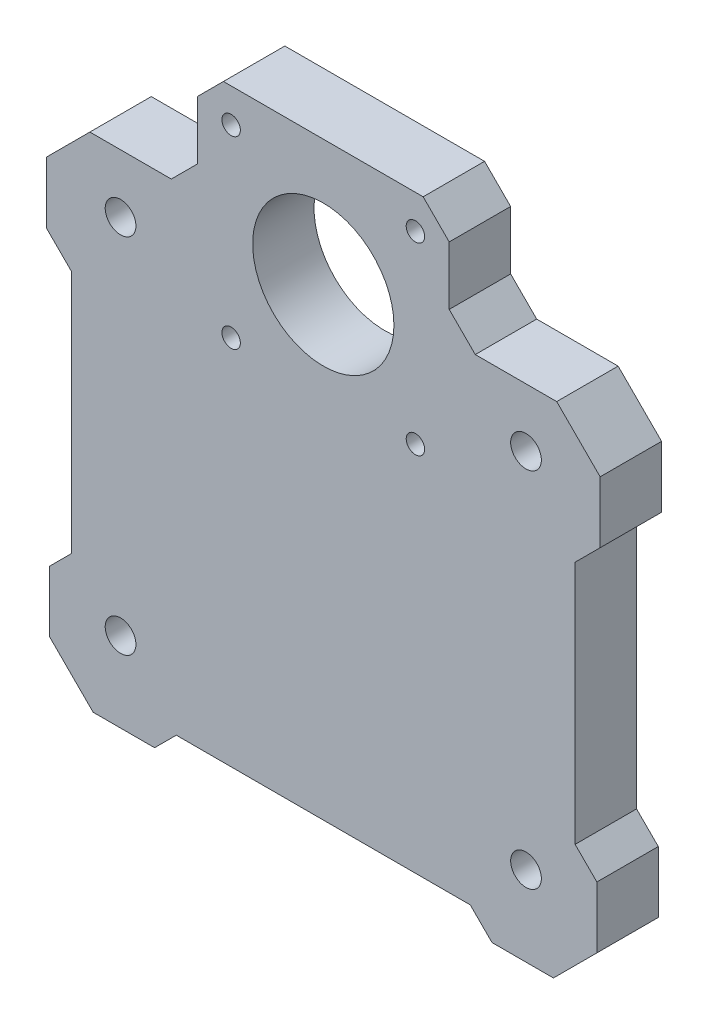
SolidWorks part; units mm, degrees
ref_plane "Alzado" through (0, 0, 0) normal (0, 0, 1) x (1, 0, 0)
ref_plane "Planta" through (0, 0, 0) normal (0, 1, 0) x (1, 0, 0)
ref_plane "Vista lateral" through (0, 0, 0) normal (1, 0, 0) x (0, 0, -1)
sketch "Croquis1" plane through (0, 0, 0) normal (0, 0, 1) x (1, 0, 0)
  line L0 (0, 0) -> (0, 36.5) construction
  line L5 (33, 29.5) -> (-33, 29.5)
  line L10 (33, 29.5) -> (33, -29.5)
  line L11 (33, -29.5) -> (-33, -29.5)
  line L12 (-33, 29.5) -> (-33, -29.5)
  line L13 (33, 29.5) -> (-33, -29.5) construction
  line L14 (33, -29.5) -> (-33, 29.5) construction
  line L15 (-41, 39) -> (41, 39)
  line L16 (-41, 39) -> (-41, -39)
  line L17 (-41, -39) -> (41, -39)
  line L18 (41, 39) -> (41, -39)
  line L19 (-41, 39) -> (41, -39) construction
  line L20 (-41, -39) -> (41, 39) construction
  line L22 (-20.5, 16) -> (20.5, 16)
  line L23 (-20.5, 16) -> (-20.5, 57)
  line L24 (-20.5, 57) -> (20.5, 57)
  line L25 (20.5, 16) -> (20.5, 57)
  line L26 (-20.5, 16) -> (20.5, 57) construction
  line L27 (-20.5, 57) -> (20.5, 16) construction
  circle A0 centre (-33, 29.5) radius 2.5
  circle A1 centre (33, 29.5) radius 2.5
  circle A2 centre (33, -29.5) radius 2.5
  circle A3 centre (-33, -29.5) radius 2.5
  circle A4 centre (0, 36.5) radius 11.5
  point P0 (0, 0)
  point P5 (0, 0)
  dimension "D5" = 36.5
  dimension "D6" = 23
  dimension "D1" = 66
  dimension "D2" = 59
  dimension "D3" = 78
  dimension "D4" = 82
  dimension "D7" = 41
  dimension "D8" = 41
extrude "Saliente-Extruir5" add sketch "Croquis1" along normal blind 10 contours A3 L11 A2 L10 A1 L5 L25 L22 L23 A0 L12 | A4 L5 L23 L22 L25 | A3 L12 A0 L5 L23 L15 L16 L17 L18 L25 A1 L10 A2 L11 | A4 L15 L25 L24 L23 | A4 L15 L23 L5 | A4 L5 L25 L15
sketch "Croquis5" plane through (0, 0, 10) normal (0, 0, 1) x (1, 0, 0)
  line L1 (-15, 51.5) -> (15, 51.5)
  line L2 (-15, 51.5) -> (-15, 21.5)
  line L3 (-15, 21.5) -> (15, 21.5)
  line L4 (15, 51.5) -> (15, 21.5)
  line L5 (-15, 51.5) -> (15, 21.5) construction
  line L6 (-15, 21.5) -> (15, 51.5) construction
  circle A0 centre (-15, 21.5) radius 1.5
  circle A1 centre (15, 21.5) radius 1.5
  circle A2 centre (15, 51.5) radius 1.5
  circle A3 centre (-15, 51.5) radius 1.5
  point P0 (0, 36.5)
  dimension "D2" = 2
  dimension "D1" = 30
  dimension "D3" = 2
extrude "Cortar-Extruir1" cut sketch "Croquis5" against normal through all contours A2 | A1 | A0 | A3
sketch "Croquis6" plane through (0, 0, 10) normal (0, 0, 1) x (1, 0, 0)
  line L0 (0, 0) -> (0, 57) construction
  line L1 (-20.5, 57) -> (20.5, 57) construction
  line L2 (-41, 39) -> (0, 39) construction
  line L3 (-38, 39) -> (38, 39)
  line L4 (20.5, 39) -> (41, 39) construction
  line L5 (38, 39) -> (45.0711, 31.9289)
  line L6 (38, 39) -> (38, -39) construction
  line L7 (-41, -39) -> (41, -39) construction
  line L8 (45.0711, 31.9289) -> (45.0711, 21.9289)
  line L9 (45.0711, 21.9289) -> (41, 17.8579)
  line L10 (41, -39) -> (44.5355, -35.4645)
  line L11 (41, 39) -> (41, -39) construction
  line L12 (44.5355, -35.4645) -> (44.5355, -25.4645)
  line L13 (45.0711, 21.9289) -> (41, 21.9289) construction
  line L14 (20.5, 43.2426) -> (24.7426, 39)
  line L15 (20.5, 39) -> (20.5, 57) construction
  line L16 (44.5355, -25.4645) -> (41, -21.9289)
  line L17 (44.5355, -35.4645) -> (37.4645, -42.5355)
  line L18 (37.4645, -42.5355) -> (27.4645, -42.5355)
  line L19 (27.4645, -42.5355) -> (23.9289, -39)
  line L20 (-45.0711, 21.9289) -> (-41, 21.9289) construction
  line L21 (-38, 39) -> (-38, -39) construction
  line L22 (-27.4645, -42.5355) -> (-23.9289, -39)
  line L23 (-37.4645, -42.5355) -> (-27.4645, -42.5355)
  line L24 (-44.5355, -35.4645) -> (-37.4645, -42.5355)
  line L25 (-44.5355, -25.4645) -> (-41, -21.9289)
  line L26 (-20.5, 43.2426) -> (-24.7426, 39)
  line L27 (-44.5355, -35.4645) -> (-44.5355, -25.4645)
  line L28 (-41, -39) -> (-44.5355, -35.4645)
  line L29 (-45.0711, 21.9289) -> (-41, 17.8579)
  line L30 (-45.0711, 31.9289) -> (-45.0711, 21.9289)
  line L31 (-38, 39) -> (-45.0711, 31.9289)
  line M21 (-20.5, 57) -> (-20.5, 39)
  line M22 (-20.5, 39) -> (-41, 39)
  line M23 (-41, 39) -> (-41, -39)
  line M24 (-41, -39) -> (41, -39)
  line M25 (41, -39) -> (41, 39)
  line M27 (20.5, 39) -> (20.5, 57)
  dimension "D1" = 17.5
  dimension "D2" = 10
  dimension "D3" = 10
  dimension "D4" = 45
  dimension "D5" = 45
  dimension "D6" = 45
  dimension "D7" = 6
  dimension "D8" = 45
  dimension "D9" = 45
  dimension "D10" = 10
  dimension "D11" = 45
extrude "Saliente-Extruir7" add sketch "Croquis6" against normal through all contours L31 L30 L29 M23 | L26 M21 M22 | L14 L3 M27 | L9 L8 L5 M25 | L12 L16 L10 M25 | L19 L18 L17 M24 | L27 L24 L25 M23 | L24 L23 L22 M24
sketch "Croquis7" plane through (0, 0, 10) normal (0, 0, 1) x (1, 0, 0)
  line L0 (-45.0711, 31.9289) -> (-38, 39)
  line L1 (-41, 39) -> (-24.7426, 39) construction
  line L2 (-38, 39) -> (-41, 39)
  line L3 (-41, 39) -> (-41, 36)
  line L4 (45.0711, 31.9289) -> (38, 39)
  line L5 (24.7426, 39) -> (41, 39) construction
  line L6 (38, 39) -> (41, 39)
  line L7 (41, 39) -> (41, 36)
  line L9 (16.2574, 57) -> (20.5, 52.7574)
  line L10 (-20.5, 57) -> (20.5, 57) construction
  line L11 (20.5, 43.2426) -> (20.5, 57) construction
  line L12 (0, 57) -> (0, 40.777) construction
  line L13 (-16.2574, 57) -> (-20.5, 52.7574)
  line L14 (-16.2574, 57) -> (-20.5, 57)
  line L15 (-20.5, 57) -> (-20.5, 52.7574)
  line L16 (16.2574, 57) -> (20.5, 57)
  line L17 (20.5, 57) -> (20.5, 52.7574)
  line M2 (41, 39) -> (24.7426, 39)
  line M4 (20.5, 43.2426) -> (20.5, 57)
  line M5 (20.5, 57) -> (-20.5, 57)
  line M6 (-20.5, 57) -> (-20.5, 43.2426)
  line M8 (-24.7426, 39) -> (-41, 39)
  line M9 (-41, 39) -> (-41, 36)
  line M29 (41, 36) -> (41, 39)
  dimension "D1" = 6
  dimension "D2" = 45
extrude "Cortar-Extruir2" cut sketch "Croquis7" against normal through all contours L13 M5 M6 | L9 M5 M4 | L0 M9 M8 | L4 M29 M2
